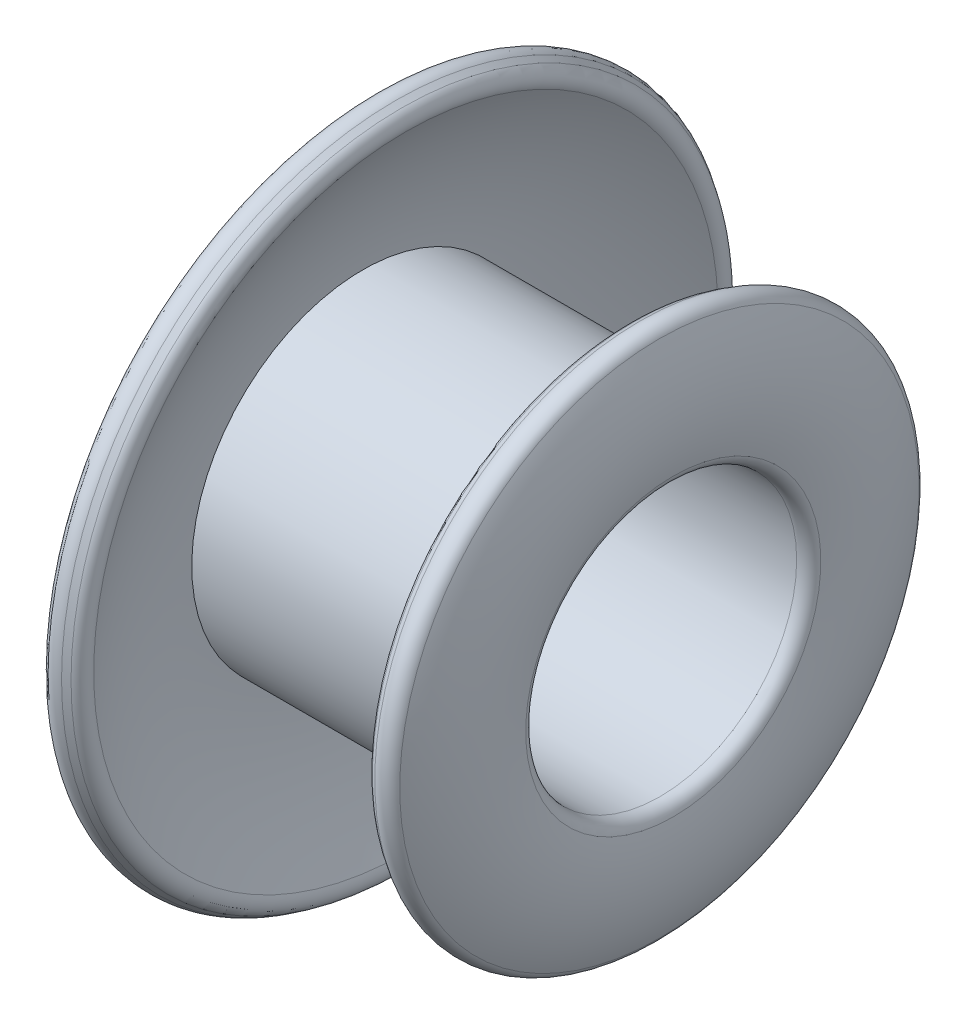
SolidWorks part; units mm, degrees
ref_plane "Front Plane" through (0, 0, 0) normal (0, 0, 1) x (1, 0, 0)
ref_plane "Top Plane" through (0, 0, 0) normal (0, 1, 0) x (1, 0, 0)
ref_plane "Right Plane" through (0, 0, 0) normal (1, 0, 0) x (0, 0, -1)
sketch "Sketch2" plane through (0, 0, 0) normal (0, 0, 1) x (1, 0, 0)
  line L0 (-0.6422, 0) -> (0.6422, 0) construction
  line L1 (-1.1569, 1) -> (1.3431, 1)
  line L2 (-0.5412, 2.3628) -> (-0.7502, 2.5)
  line L3 (-0.9069, 1.25) -> (1.1368, 1.25)
  line L4 (1.3431, 1) -> (-1.1569, 1)
  line L5 (-1.1569, 1) -> (1.0931, 1) construction
  line L6 (-0.9069, 1.25) -> (1.0931, 1.25) construction
  line L7 (0.9952, 1.8631) -> (1.2088, 1.9932)
  arc A0 (-1.1569, 1) -> (-0.7502, 2.5) centre (1.3398, 1.1283) cw
  arc A1 (-0.9069, 1.25) -> (-0.5412, 2.3628) centre (1.3398, 1.1283) cw
  arc A2 (1.3431, 1) -> (1.2088, 1.9932) centre (0.1411, 1.3431) ccw
  arc A3 (1.1368, 1.25) -> (0.9952, 1.8631) centre (0.1411, 1.3431) ccw
  arc A4 (1.1027, 1.0686) -> (0.9952, 1.8631) centre (0.1411, 1.3431) ccw construction
  point P11 (0, 0)
  dimension "D6" = 2.5
  dimension "D5" = 1.5
  dimension "D2" = 0.25
  dimension "D3" = 1.25
  dimension "D4" = 1.75
  dimension "D7" = 0.25
  dimension "D9" = 0.25
revolve "Revolve1" add sketch "Sketch2" angle 360 about L0
fillet "Fillet1" radius 0.1 6 edges at (-0.5412, -2.3628, 0) (-1.1569, -1, 0) (-0.7502, -2.5, 0) (1.3431, -1, 0) (1.2088, -1.9932, 0) (0.9952, -1.8631, 0)
